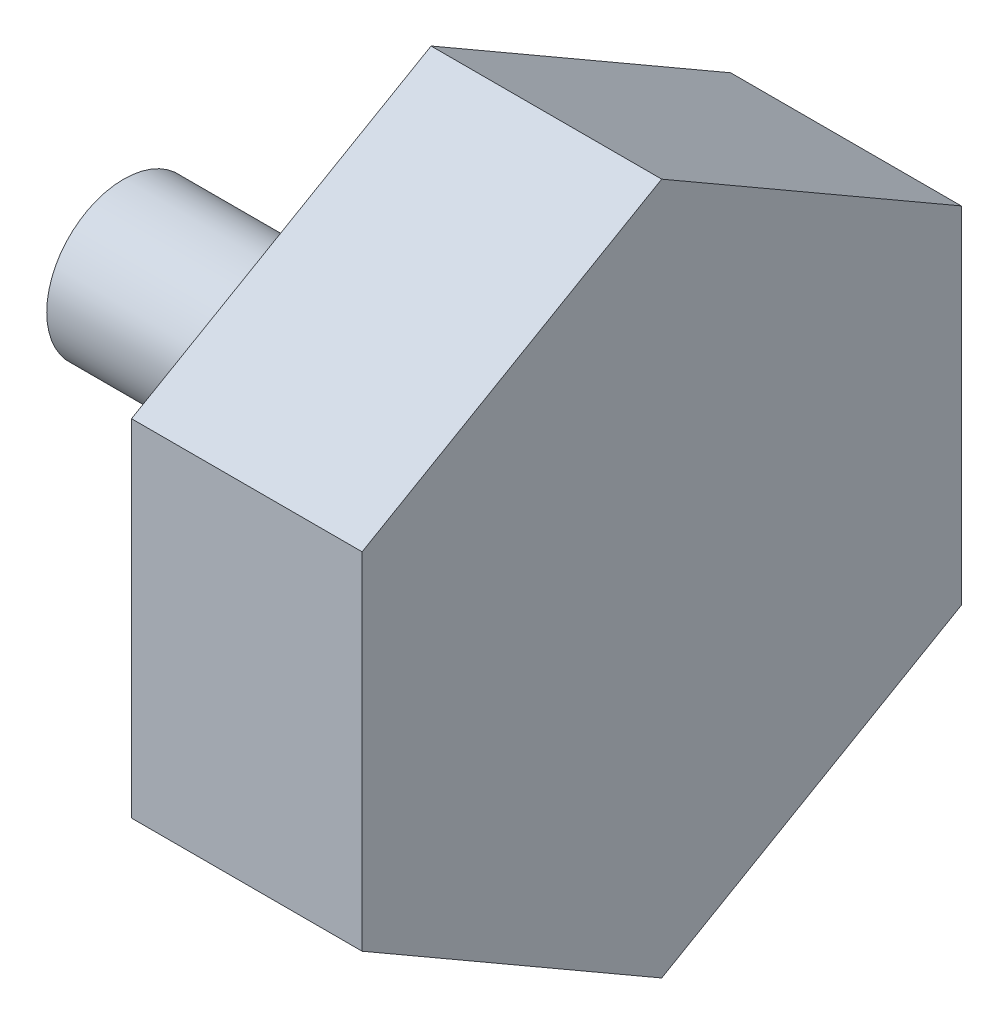
SolidWorks part; units mm, degrees
ref_plane "Front Plane" through (0, 0, 0) normal (0, 0, 1) x (1, 0, 0)
ref_plane "Top Plane" through (0, 0, 0) normal (0, 1, 0) x (1, 0, 0)
ref_plane "Right Plane" through (0, 0, 0) normal (1, 0, 0) x (0, 0, -1)
sketch "Sketch1" plane through (0, 0, 0) normal (1, 0, 0) x (0, 0, -1)
  line L1 (0, -9) -> (7.7942, -4.5)
  line L2 (7.7942, -4.5) -> (7.7942, 4.5)
  line L3 (7.7942, 4.5) -> (0, 9)
  line L4 (0, 9) -> (-7.7942, 4.5)
  line L5 (-7.7942, 4.5) -> (-7.7942, -4.5)
  line L6 (-7.7942, -4.5) -> (0, -9)
  circle A0 centre (0, 0) radius 7.7942 construction
  dimension "D1" = 9
extrude "Boss-Extrude1" add sketch "Sketch1" along normal blind 6
sketch "Sketch2" plane through (0, 0, 0) normal (-1, 0, 0) x (0, 0, 1)
  circle A0 centre (0, 0) radius 2
  dimension "D1" = 4
extrude "Boss-Extrude2" add sketch "Sketch2" along normal blind 8
cosmetic thread "Cosmetic Thread1" parameters "D1"=4.3, "D2"=3.22
